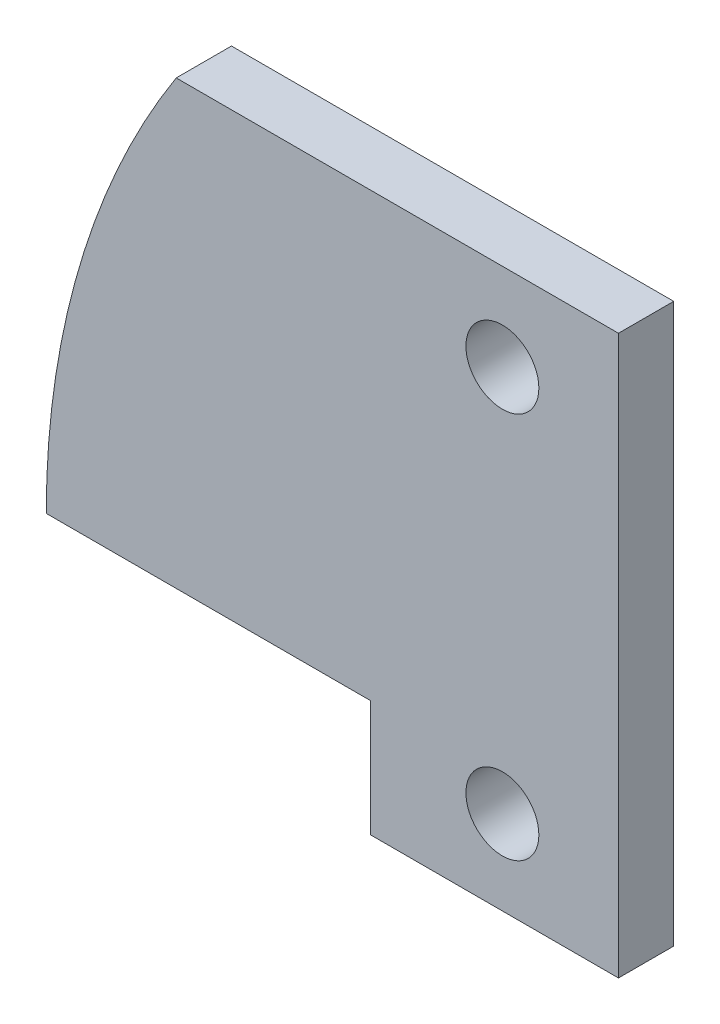
SolidWorks part; units mm, degrees
ref_plane "Front Plane" through (0, 0, 0) normal (0, 0, 1) x (1, 0, 0)
ref_plane "Top Plane" through (0, 0, 0) normal (0, 1, 0) x (1, 0, 0)
ref_plane "Right Plane" through (0, 0, 0) normal (1, 0, 0) x (0, 0, -1)
sketch "Sketch1" plane through (0, 0, 0) normal (0, 0, 1) x (1, 0, 0)
  line L11 (-8.0046, 23.2577) -> (12, 23.2577)
  line L12 (12, 23.2577) -> (12, 0)
  line L14 (0.7757, 0) -> (0.7757, -2)
  line L15 (0.7757, -2) -> (12, -2)
  line L16 (12, -2) -> (12, 0)
  line L17 (-13.8827, 3.2577) -> (0.7757, 3.2577)
  line L18 (0.7757, 3.2577) -> (0.7757, 0)
  circle A2 centre (6.7492, 19.3061) radius 1.65
  circle A3 centre (6.7492, 1.8061) radius 1.65
  arc A4 (-13.8827, 3.2577) -> (-8.0046, 23.2577) centre (23.081, 3.2577) cw
  point P16 (6.7492, 19.3061)
  dimension "D1" = 20
  dimension "D3" = 36.9636
  dimension "D2" = 3.3
  dimension "D7" = 23.081
  dimension "D8" = 1.8061
  dimension "D4" = 0.7757
  dimension "D5" = 6.7492
  dimension "D6" = 12
  dimension "D9" = 3.2577
  dimension "D10" = 19.3061
  dimension "D12" = 2
extrude "Boss-Extrude1" add sketch "Sketch1" along normal blind 2.5
